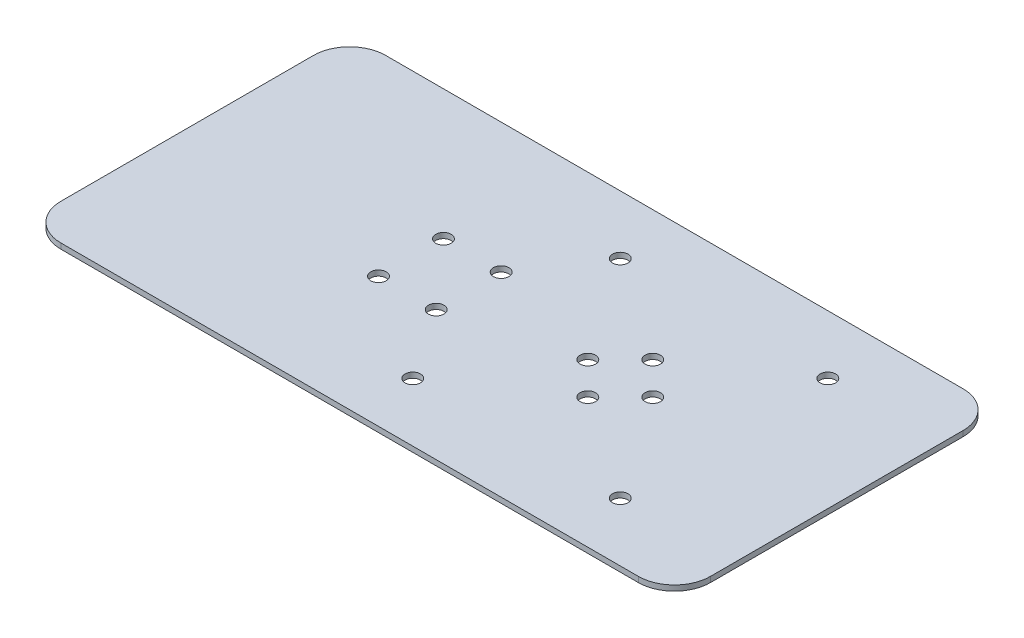
SolidWorks part; units mm, degrees
ref_plane "Front Plane" through (0, 0, 0) normal (0, 0, 1) x (1, 0, 0)
ref_plane "Top Plane" through (0, 0, 0) normal (0, 1, 0) x (1, 0, 0)
ref_plane "Right Plane" through (0, 0, 0) normal (1, 0, 0) x (0, 0, -1)
sketch "Sketch1" plane through (0, 0, 0) normal (0, 1, 0) x (1, 0, 0)
  line L1 (0, 0) -> (180, 0)
  line L2 (0, 0) -> (0, -120)
  line L3 (0, -120) -> (180, -120)
  line L4 (180, 0) -> (180, -120)
  dimension "D1" = 120
  dimension "D2" = 180
extrude "Boss-Extrude1" add sketch "Sketch1" along normal blind 1.5
sketch "Sketch2" plane through (0, 1.5, 0) normal (0, 1, 0) x (1, 0, 0)
  line L0 (180, -120) -> (180, 0) construction
  line L1 (180, 0) -> (0, 0) construction
  circle A0 centre (120, -51) radius 2.15
  circle A1 centre (120, -69) radius 2.15
  circle A2 centre (129, -60) radius 2.15
  circle A3 centre (111, -60) radius 2.15
  circle A4 centre (78, -51) radius 2.15
  circle A5 centre (62, -51) radius 2.15
  circle A6 centre (62, -69) radius 2.15
  circle A7 centre (78, -69) radius 2.15
  circle A8 centre (148.75, -31.25) radius 2.15
  circle A9 centre (91.25, -31.25) radius 2.15
  circle A10 centre (91.25, -88.75) radius 2.15
  circle A11 centre (148.75, -88.75) radius 2.15
  dimension "D1" = 4.3
  dimension "D2" = 60
  dimension "D3" = 18
  dimension "D4" = 51
  dimension "D5" = 60
  dimension "D6" = 18
  dimension "D7" = 51
  dimension "D8" = 42
  dimension "D9" = 16
  dimension "D10" = 28.75
  dimension "D11" = 28.75
  dimension "D12" = 28.75
  dimension "D13" = 28.75
extrude "Cut-Extrude1" cut sketch "Sketch2" against normal through all
sketch "Sketch3" plane through (0, 1.5, 0) normal (0, 1, 0) x (1, 0, 0)
  line L0 (180, -120) -> (180, 0) construction
  line L1 (0, 0) -> (180, 0)
  line L2 (0, 0) -> (0, -15)
  line L3 (0, -15) -> (180, -15)
  line L4 (180, 0) -> (180, -15)
  line L6 (0, -120) -> (180, -120)
  line L7 (0, -120) -> (0, -105)
  line L8 (0, -105) -> (180, -105)
  line L9 (180, -120) -> (180, -105)
  dimension "D1" = 15
  dimension "D2" = 15
extrude "Cut-Extrude2" cut sketch "Sketch3" against normal through all
fillet "Fillet1" radius 10 4 edges at (0, 0.75, 15) (180, 0.75, 15) (180, 0.75, 105) (0, 0.75, 105)
